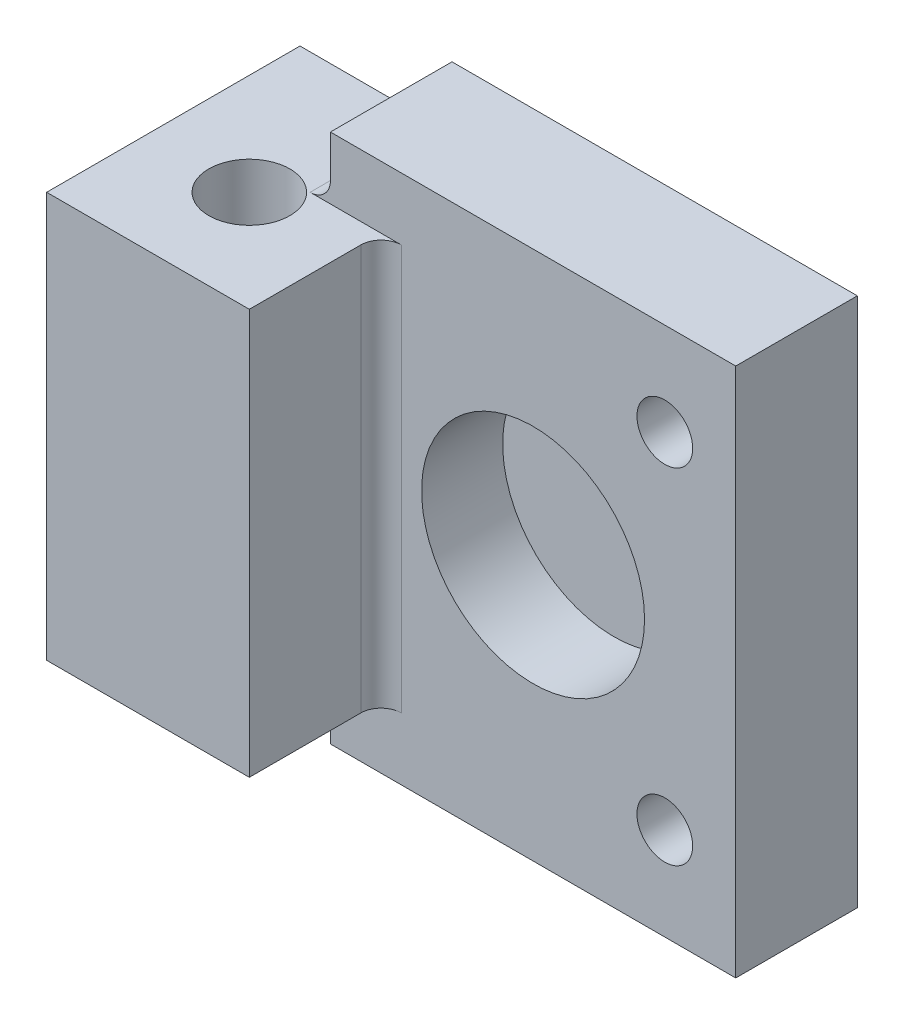
SolidWorks part; units mm, degrees
ref_plane "Front Plane" through (0, 0, 0) normal (0, 0, 1) x (1, 0, 0)
ref_plane "Top Plane" through (0, 0, 0) normal (0, 1, 0) x (1, 0, 0)
ref_plane "Right Plane" through (0, 0, 0) normal (1, 0, 0) x (0, 0, -1)
sketch "Sketch1" plane through (0, 0, 0) normal (0, 0, 1) x (1, 0, 0)
  line L1 (20, 26.15) -> (-20, 26.15)
  line L2 (20, 26.15) -> (20, -26.15)
  line L3 (20, -26.15) -> (-20, -26.15)
  line L4 (-20, 26.15) -> (-20, -26.15)
  line L5 (20, 26.15) -> (-20, -26.15) construction
  line L6 (20, -26.15) -> (-20, 26.15) construction
  circle A0 centre (13, 16.9975) radius 2.75
  circle A1 centre (13, -16.9975) radius 2.75
  point P0 (0, 0)
  dimension "D1" = 52.3
  dimension "D6" = 7
  dimension "D3" = 5.5
  dimension "D2" = 40
  dimension "D5" = 7
extrude "Boss-Extrude1" add sketch "Sketch1" along normal blind 12
sketch "Sketch2" plane through (0, 0, 12) normal (0, 0, 1) x (1, 0, 0)
  circle A0 centre (0, 0) radius 11
  dimension "D1" = 22
extrude "Cut-Extrude1" cut sketch "Sketch2" against normal blind 8
ref_plane "Plane1" through (-15, 0, 0) normal (-1, 0, 0) x (0, 0, 1)
sketch "Sketch6" plane through (-15, 0, 0) normal (-1, 0, 0) x (0, 0, 1)
  line L0 (0, 26.15) -> (0, -26.15) construction
  line L1 (0, 20) -> (25, 20)
  line L2 (0, 20) -> (0, -20)
  line L3 (0, -20) -> (25, -20)
  line L4 (25, 20) -> (25, -20)
  point P6 (0, 0)
  dimension "D1" = 40
  dimension "D2" = 25
extrude "Boss-Extrude3" add sketch "Sketch6" along normal blind 20
sketch "Sketch7" plane through (0, 20, 0) normal (0, 1, 0) x (1, 0, 0)
  line L0 (-35, 0) -> (-20, 0) construction
  line L1 (-35, -25) -> (-35, 0) construction
  circle A0 centre (-25, -15) radius 4
  dimension "D2" = 8
  dimension "D1" = 15
  dimension "D3" = 10
extrude "Cut-Extrude3" cut sketch "Sketch7" against normal blind 35
fillet "Fillet1" radius 2 2 edges at (-20, 20, 6) (-20, -20, 6)
fillet "Fillet2" radius 2 1 edges at (-15, 0, 12)
